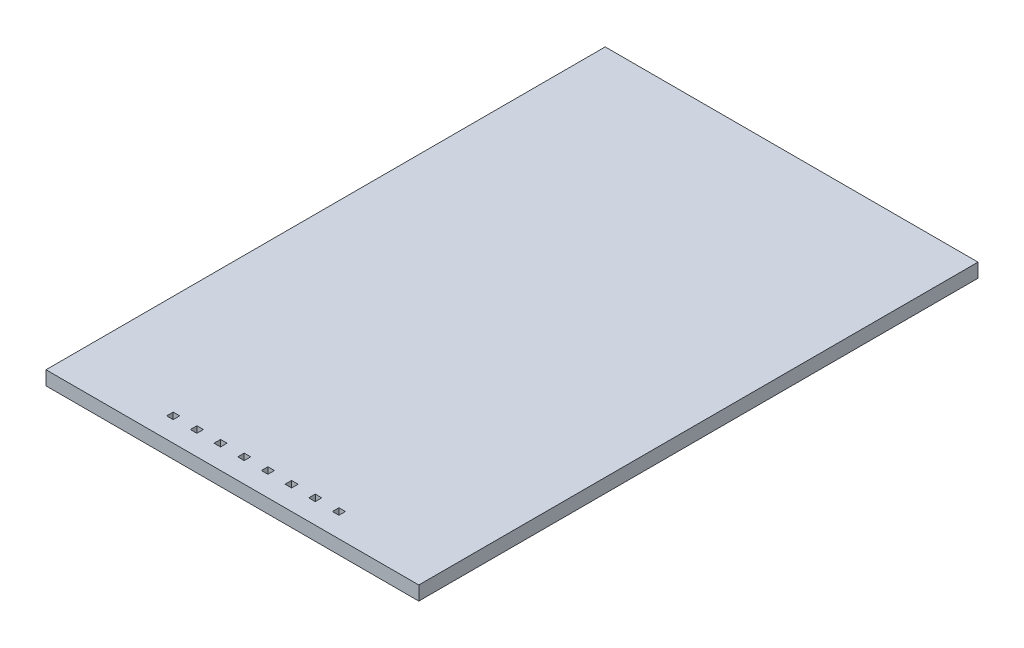
SolidWorks part; units mm, degrees
ref_plane "Front" through (0, 0, 0) normal (0, 0, 1) x (1, 0, 0)
ref_plane "Top" through (0, 0, 0) normal (0, 1, 0) x (1, 0, 0)
ref_plane "Right" through (0, 0, 0) normal (1, 0, 0) x (0, 0, -1)
sketch "Эскиз2" plane through (0, 0, 0) normal (0, 1, 0) x (1, 0, 0)
  line L1 (-20, 30) -> (20, 30)
  line L2 (-20, 30) -> (-20, -30)
  line L3 (-20, -30) -> (20, -30)
  line L4 (20, 30) -> (20, -30)
  line L5 (-20, 30) -> (20, -30) construction
  line L6 (-20, -30) -> (20, 30) construction
  point P0 (0, 0)
extrude "Бобышка-Вытянуть1" add sketch "Эскиз2" along normal blind 1.5
sketch "Эскиз3" plane through (0, 1.5, 0) normal (0, 1, 0) x (1, 0, 0)
  line L0 (0, -30) -> (0, -27.46) construction
  line L1 (-20, -30) -> (20, -30) construction
  line L2 (0, -27.46) -> (-1.27, -27.46) construction
  line L3 (0, -27.46) -> (1.27, -27.46) construction
  line L4 (-3.46, -27.11) -> (-4.16, -27.11)
  line L5 (-0.92, -27.11) -> (-1.62, -27.11)
  line L6 (-0.92, -27.11) -> (-0.92, -27.81)
  line L7 (-0.92, -27.81) -> (-1.62, -27.81)
  line L8 (-1.62, -27.11) -> (-1.62, -27.81)
  line L9 (-0.92, -27.11) -> (-1.62, -27.81) construction
  line L10 (-0.92, -27.81) -> (-1.62, -27.11) construction
  line L11 (-3.46, -27.11) -> (-3.46, -27.81)
  line L12 (-3.46, -27.81) -> (-4.16, -27.81)
  line L13 (-4.16, -27.11) -> (-4.16, -27.81)
  line L14 (-3.46, -27.11) -> (-4.16, -27.81) construction
  line L15 (-3.46, -27.81) -> (-4.16, -27.11) construction
  line L16 (-6, -27.11) -> (-6.7, -27.11)
  line L17 (-6, -27.11) -> (-6, -27.81)
  line L18 (-6, -27.81) -> (-6.7, -27.81)
  line L19 (-6.7, -27.11) -> (-6.7, -27.81)
  line L20 (-6, -27.11) -> (-6.7, -27.81) construction
  line L21 (-6, -27.81) -> (-6.7, -27.11) construction
  line L22 (-8.54, -27.11) -> (-9.24, -27.11)
  line L23 (-8.54, -27.11) -> (-8.54, -27.81)
  line L24 (-8.54, -27.81) -> (-9.24, -27.81)
  line L25 (-9.24, -27.11) -> (-9.24, -27.81)
  line L26 (-8.54, -27.11) -> (-9.24, -27.81) construction
  line L27 (-8.54, -27.81) -> (-9.24, -27.11) construction
  line L28 (8.54, -27.81) -> (9.24, -27.11) construction
  line L29 (8.54, -27.11) -> (9.24, -27.81) construction
  line L30 (6, -27.81) -> (6.7, -27.11) construction
  line L31 (6, -27.11) -> (6.7, -27.81) construction
  line L32 (3.46, -27.81) -> (4.16, -27.11) construction
  line L33 (3.46, -27.11) -> (4.16, -27.81) construction
  line L34 (0.92, -27.81) -> (1.62, -27.11) construction
  line L35 (0.92, -27.11) -> (1.62, -27.81) construction
  line L36 (9.24, -27.11) -> (9.24, -27.81)
  line L37 (8.54, -27.81) -> (9.24, -27.81)
  line L38 (8.54, -27.11) -> (8.54, -27.81)
  line L39 (8.54, -27.11) -> (9.24, -27.11)
  line L40 (6.7, -27.11) -> (6.7, -27.81)
  line L41 (6, -27.81) -> (6.7, -27.81)
  line L42 (6, -27.11) -> (6, -27.81)
  line L43 (6, -27.11) -> (6.7, -27.11)
  line L44 (4.16, -27.11) -> (4.16, -27.81)
  line L45 (3.46, -27.81) -> (4.16, -27.81)
  line L46 (3.46, -27.11) -> (3.46, -27.81)
  line L47 (1.62, -27.11) -> (1.62, -27.81)
  line L48 (0.92, -27.81) -> (1.62, -27.81)
  line L49 (0.92, -27.11) -> (0.92, -27.81)
  line L50 (0.92, -27.11) -> (1.62, -27.11)
  line L51 (3.46, -27.11) -> (4.16, -27.11)
  dimension "D1" = 4
extrude "Вырез-Вытянуть1" cut sketch "Эскиз3" against normal through all
